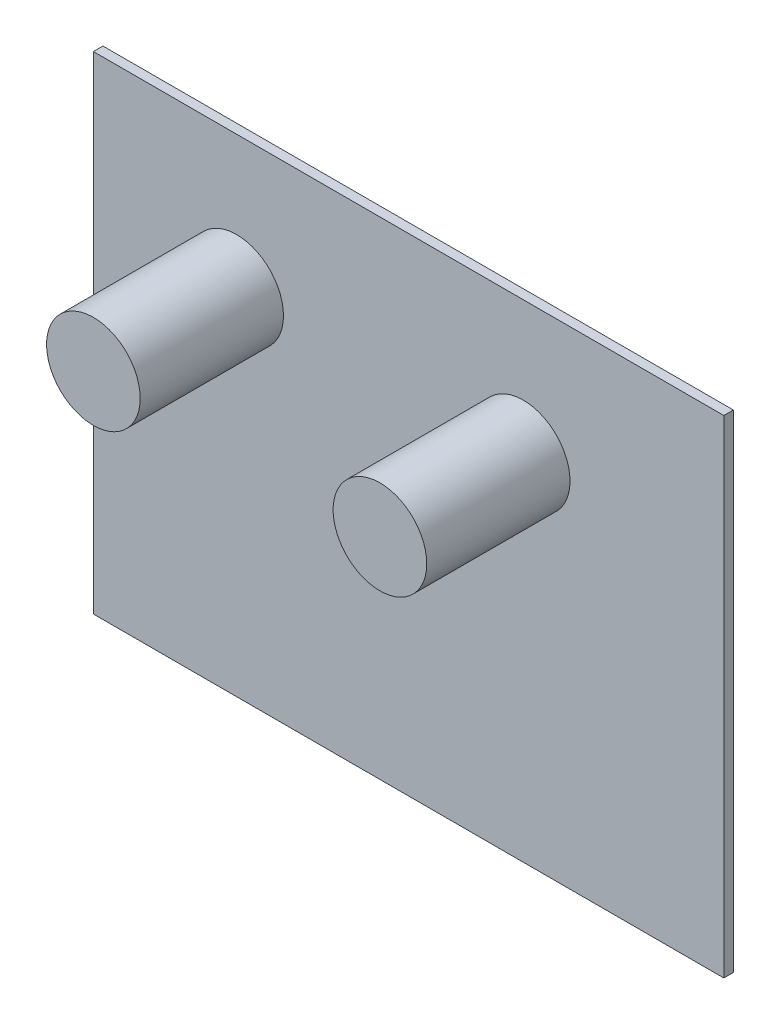
SolidWorks part; units mm, degrees
ref_plane "Plan de face" through (0, 0, 0) normal (0, 0, 1) x (1, 0, 0)
ref_plane "Plan de dessus" through (0, 0, 0) normal (0, 1, 0) x (1, 0, 0)
ref_plane "Plan de droite" through (0, 0, 0) normal (1, 0, 0) x (0, 0, -1)
sketch "Esquisse2" plane through (0, 0, 0) normal (0, 0, 1) x (1, 0, 0)
  line L1 (0, 0) -> (66, 0)
  line L2 (0, 0) -> (0, 51)
  line L3 (0, 51) -> (66, 51)
  line L4 (66, 0) -> (66, 51)
  line L5 (5, 46) -> (25, 46)
  line L6 (5, 46) -> (5, 5)
  line L7 (5, 5) -> (25, 5)
  line L8 (25, 46) -> (25, 5)
  circle A0 centre (15, 37) radius 4.9
  circle A1 centre (55, 37) radius 4.9
  circle A2 centre (55, 37) radius 6
  dimension "D1" = 9.8
  dimension "D2" = 9.8
  dimension "D11" = 12
  dimension "D13" = 11
  dimension "D3" = 20
  dimension "D4" = 41
  dimension "D5" = 10
  dimension "D6" = 9
  dimension "D7" = 9
  dimension "D8" = 40
  dimension "D9" = 5
  dimension "D10" = 5
  dimension "D12" = 5
extrude "Boss.-Extru.1" add sketch "Esquisse2" along normal blind 1 contours L1 L4 L3 L2 A2 L5 L8 L7 L6 | L8 L5 L6 L7 A0 | A0 | A1 | A2 A1
sketch "Esquisse4" plane through (0, 0, 1) normal (0, 0, 1) x (1, 0, 0)
  line L0 (0, 0) -> (56, 0)
  line L1 (0, 0) -> (0, 51)
  line L2 (0, 51) -> (56, 51)
  line L3 (56, 0) -> (56, 51)
  line L4 (5, 46) -> (25, 46)
  line L5 (5, 46) -> (5, 5)
  line L6 (5, 5) -> (25, 5)
  line L7 (25, 46) -> (25, 5)
  circle A0 centre (15, 37) radius 4.9
  circle A1 centre (45, 37) radius 4.9
  circle A2 centre (45, 37) radius 6
  dimension "D1" = 9.8
  dimension "D2" = 9.8
  dimension "D10" = 12
  dimension "D3" = 20
  dimension "D4" = 41
  dimension "D5" = 10
  dimension "D6" = 9
  dimension "D7" = 9
  dimension "D8" = 30
  dimension "D9" = 5
  dimension "D11" = 5
  dimension "D12" = 5
  dimension "D13" = 11
extrude "Boss.-Extru.2" add sketch "Esquisse4" along normal blind 15 contours A0 | A1
